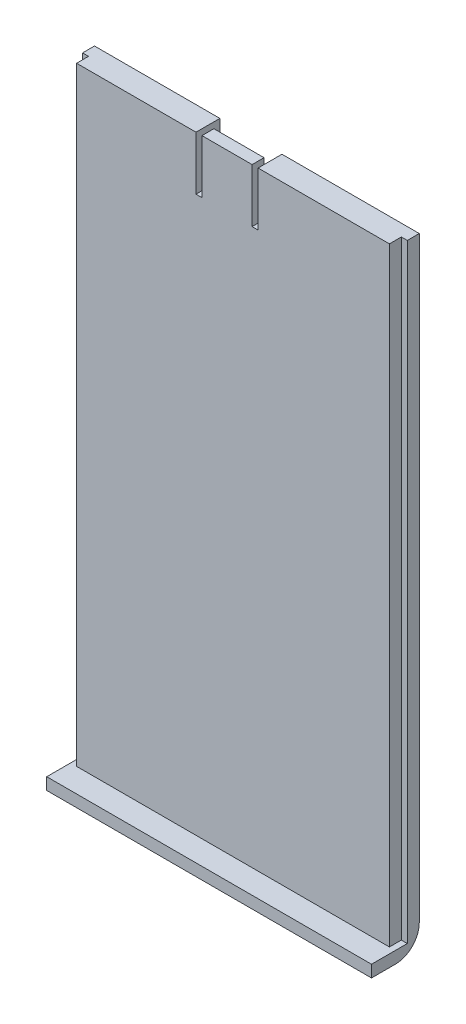
SolidWorks part; units mm, degrees
ref_plane "Front Plane" through (0, 0, 0) normal (0, 0, 1) x (1, 0, 0)
ref_plane "Top Plane" through (0, 0, 0) normal (0, 1, 0) x (1, 0, 0)
ref_plane "Right Plane" through (0, 0, 0) normal (1, 0, 0) x (0, 0, -1)
sketch "Sketch1" plane through (0, 0, 0) normal (0, 0, 1) x (1, 0, 0)
  line L1 (0, 0) -> (27.2, 0)
  line L2 (0, 0) -> (0, 52)
  line L3 (0, 52) -> (27.2, 52)
  line L4 (27.2, 0) -> (27.2, 52)
  dimension "D1" = 27.2
  dimension "D2" = 52
extrude "Boss-Extrude1" add sketch "Sketch1" along normal blind 2
sketch "Sketch2" plane through (0, 0, 2) normal (0, 0, 1) x (1, 0, 0)
  line L0 (0, 0) -> (27.2, 0) construction
  line L1 (0, 52) -> (0.5, 52)
  line L2 (0, 52) -> (0, 0)
  line L3 (0, 0) -> (0.5, 0)
  line L4 (0.5, 52) -> (0.5, 0)
  dimension "D1" = 0.5
extrude "Cut-Extrude1" cut sketch "Sketch2" against normal blind 1
sketch "Sketch3" plane through (0, 0, 2) normal (0, 0, 1) x (1, 0, 0)
  line L0 (27.2, 52) -> (0.5, 52) construction
  line L1 (27.2, 0) -> (26.7, 0)
  line L2 (27.2, 0) -> (27.2, 52)
  line L3 (27.2, 52) -> (26.7, 52)
  line L4 (26.7, 0) -> (26.7, 52)
  dimension "D1" = 0.5
extrude "Cut-Extrude2" cut sketch "Sketch3" against normal blind 1
sketch "Sketch4" plane through (0, 52, 0) normal (0, 1, 0) x (1, 0, 0)
  line L0 (27.2, 0) -> (0, 0) construction
  line L1 (10.5, 0) -> (11, 0)
  line L2 (10.5, 0) -> (10.5, -2)
  line L3 (10.5, -2) -> (11, -2)
  line L4 (11, 0) -> (11, -2)
  line L5 (26.7, -2) -> (0.5, -2) construction
  line L6 (0, -1) -> (0, 0) construction
  dimension "D1" = 10.5
  dimension "D2" = 0.5
extrude "Cut-Extrude3" cut sketch "Sketch4" against normal blind 4.5
sketch "Sketch5" plane through (0, 52, 0) normal (0, 1, 0) x (1, 0, 0)
  line L0 (27.2, 0) -> (11, 0) construction
  line L1 (15.2, 0) -> (15.7, 0)
  line L2 (15.2, 0) -> (15.2, -2)
  line L3 (15.2, -2) -> (15.7, -2)
  line L4 (15.7, 0) -> (15.7, -2)
  line L5 (26.7, -2) -> (11, -2) construction
  line L6 (27.2, -1) -> (27.2, 0) construction
  dimension "D1" = 0.5
  dimension "10.5" = 11.5
extrude "Cut-Extrude4" cut sketch "Sketch5" against normal blind 4.5
sketch "Sketch6" plane through (0, 52, 0) normal (0, 1, 0) x (1, 0, 0)
  line L0 (15.2, 0) -> (15.2, -2) construction
  line L1 (11, 0) -> (15.2, 0)
  line L2 (11, 0) -> (11, -1)
  line L3 (11, -1) -> (15.2, -1)
  line L4 (15.2, 0) -> (15.2, -1)
  dimension "D1" = 1
extrude "Cut-Extrude5" cut sketch "Sketch6" against normal blind 4.5
sketch "Sketch9" plane through (0, 0, 0) normal (0, 0, -1) x (-1, 0, 0)
  line L0 (0, 52) -> (0, 0) construction
  line L1 (-27.2, 0) -> (0, 0)
  line L2 (-27.2, 0) -> (-27.2, 1)
  line L3 (-27.2, 1) -> (0, 1)
  line L4 (0, 0) -> (0, 1)
  dimension "D1" = 1
extrude "Boss-Extrude3" add sketch "Sketch9" against normal blind 4
fillet "Fillet1" radius 2 1 edges at (13.6, 0, 0)
